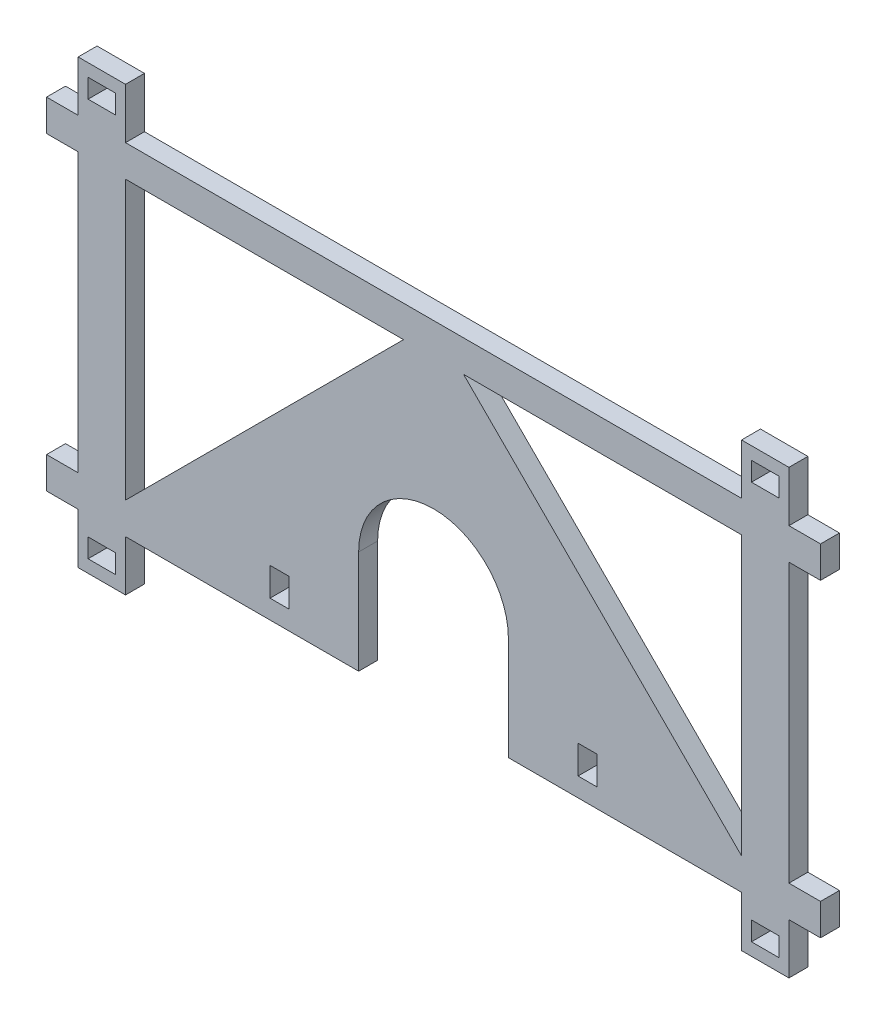
SolidWorks part; units mm, degrees
ref_plane "Front Plane" through (0, 0, 0) normal (0, 0, 1) x (1, 0, 0)
ref_plane "Top Plane" through (0, 0, 0) normal (0, 1, 0) x (1, 0, 0)
ref_plane "Right Plane" through (0, 0, 0) normal (1, 0, 0) x (0, 0, -1)
sketch "Sketch1" plane through (0, 0, 0) normal (0, 0, 1) x (1, 0, 0)
  line L0 (198.9667, 91.44) -> (198.9667, 82.9733)
  line L5 (198.9667, 82.9733) -> (190.5, 82.9733)
  line L6 (190.5, 0) -> (198.9667, 0)
  line L7 (198.9667, 0) -> (198.9667, 8.4667)
  line L8 (198.9667, 8.4667) -> (190.5, 8.4667)
  line L9 (-8.4667, 91.44) -> (-8.4667, 82.9733)
  line L10 (-8.4667, 82.9733) -> (0, 82.9733)
  line L11 (-8.4667, 91.44) -> (0, 91.44)
  line L12 (0, 0) -> (-8.4667, 0)
  line L13 (-8.4667, 0) -> (-8.4667, 8.4667)
  line L14 (-8.4667, 8.4667) -> (0, 8.4667)
  line L15 (0, 91.44) -> (0, 82.9733) construction
  line L16 (190.5, 91.44) -> (190.5, 82.9733) construction
  line L17 (190.5, 8.4667) -> (190.5, 0) construction
  line L18 (0, 8.4667) -> (0, 0) construction
  line L19 (198.9667, 91.44) -> (190.5, 91.44)
  line L20 (0, 82.9733) -> (0, 8.4667)
  line L21 (190.5, 82.9733) -> (190.5, 8.4667)
  line L22 (0, 0) -> (0, -13.5467)
  line L23 (0, -13.5467) -> (12.7, -13.5467)
  line L24 (12.7, -13.5467) -> (12.7, 0)
  line L25 (190.5, 0) -> (190.5, -13.5467)
  line L26 (190.5, -13.5467) -> (177.8, -13.5467)
  line L27 (177.8, -13.5467) -> (177.8, 0)
  line L28 (190.5, 91.44) -> (190.5, 104.9867)
  line L29 (190.5, 104.9867) -> (177.8, 104.9867)
  line L30 (177.8, 104.9867) -> (177.8, 91.44)
  line L31 (0, 91.44) -> (0, 104.9867)
  line L32 (0, 104.9867) -> (12.7, 104.9867)
  line L33 (12.7, 104.9867) -> (12.7, 91.44)
  line L34 (0, 91.44) -> (12.7, 91.44) construction
  line L35 (177.8, 91.44) -> (190.5, 91.44) construction
  line L36 (177.8, 0) -> (190.5, 0) construction
  line L37 (0, 0) -> (12.7, 0) construction
  line L38 (12.7, 91.44) -> (177.8, 91.44)
  line L39 (12.7, 0) -> (177.8, 0)
  dimension "D1" = 190.5
  dimension "D2" = 91.44
  dimension "D3" = 8.4667
  dimension "D4" = 8.4667
  dimension "D5" = 13.5467
  dimension "D6" = 12.7
extrude "Boss-Extrude1" add sketch "Sketch1" along normal blind 5.08
sketch "Sketch2" plane through (0, 0, 5.08) normal (0, 0, 1) x (1, 0, 0)
  line L0 (95.25, 0) -> (95.25, 47.752) construction
  line L1 (12.7, 0) -> (177.8, 0) construction
  line L2 (95.25, 0) -> (115.316, 0)
  line L3 (115.316, 0) -> (115.316, 27.686)
  line L5 (75.184, 27.686) -> (75.184, 0)
  line L6 (95.25, 0) -> (75.184, 0)
  line L7 (75.184, 0) -> (115.316, 0) construction
  arc A0 (115.316, 27.686) -> (75.184, 27.686) centre (95.25, 27.686) ccw
  dimension "D1" = 47.752
  dimension "D2" = 20.066
extrude "Cut-Extrude2" cut sketch "Sketch2" against normal through all
sketch "Sketch3" plane through (0, 0, 5.08) normal (0, 0, 1) x (1, 0, 0)
  line L0 (177.8, 91.44) -> (190.5, 91.44) construction
  line L1 (177.8, 0) -> (190.5, 0) construction
  line L2 (0, 0) -> (12.7, 0) construction
  line L3 (0, 91.44) -> (12.7, 91.44) construction
  line L4 (6.35, 91.44) -> (6.35, 96.52) construction
  line L5 (184.15, 91.44) -> (184.15, 96.52) construction
  line L6 (184.15, 0) -> (184.15, -5.08) construction
  line L7 (6.35, 0) -> (6.35, -5.08) construction
  line L8 (6.35, 96.52) -> (10.033, 96.52)
  line L9 (10.033, 96.52) -> (10.033, 101.6)
  line L10 (10.033, 101.6) -> (2.667, 101.6)
  line L11 (2.667, 101.6) -> (2.667, 96.52)
  line L12 (2.667, 96.52) -> (6.35, 96.52)
  line L13 (184.15, 96.52) -> (187.833, 96.52)
  line L14 (187.833, 96.52) -> (187.833, 101.6)
  line L15 (187.833, 101.6) -> (180.467, 101.6)
  line L16 (180.467, 101.6) -> (180.467, 96.52)
  line L17 (180.467, 96.52) -> (184.15, 96.52)
  line L18 (184.15, -5.08) -> (187.833, -5.08)
  line L19 (187.833, -5.08) -> (187.833, -10.16)
  line L20 (187.833, -10.16) -> (180.467, -10.16)
  line L21 (180.467, -10.16) -> (180.467, -5.08)
  line L22 (180.467, -5.08) -> (184.15, -5.08)
  line L23 (6.35, -5.08) -> (10.033, -5.08)
  line L24 (10.033, -5.08) -> (10.033, -10.16)
  line L25 (10.033, -10.16) -> (2.667, -10.16)
  line L26 (2.667, -10.16) -> (2.667, -5.08)
  line L27 (2.667, -5.08) -> (6.35, -5.08)
  dimension "D1" = 5.08
  dimension "D2" = 5.08
  dimension "D3" = 3.683
extrude "Cut-Extrude4" cut sketch "Sketch3" against normal through all
sketch "Sketch4" plane through (0, 0, 5.08) normal (0, 0, 1) x (1, 0, 0)
  line L0 (12.7, 0) -> (53.975, 0) construction
  line L1 (12.7, 0) -> (75.184, 0) construction
  line L2 (53.975, 0) -> (95.25, 0) construction
  line L3 (95.25, 0) -> (136.525, 0) construction
  line L4 (115.316, 0) -> (177.8, 0) construction
  line L5 (136.525, 0) -> (177.8, 0) construction
  line L6 (53.975, 0) -> (53.975, 5.08) construction
  line L7 (136.525, 0) -> (136.525, 5.08) construction
  line L8 (136.525, 5.08) -> (139.065, 5.08)
  line L9 (139.065, 5.08) -> (139.065, 12.7)
  line L10 (139.065, 12.7) -> (133.985, 12.7)
  line L11 (133.985, 12.7) -> (133.985, 5.08)
  line L12 (133.985, 5.08) -> (136.525, 5.08)
  line L13 (53.975, 5.08) -> (56.515, 5.08)
  line L14 (56.515, 5.08) -> (56.515, 12.7)
  line L15 (56.515, 12.7) -> (51.435, 12.7)
  line L16 (51.435, 12.7) -> (51.435, 5.08)
  line L17 (51.435, 5.08) -> (53.975, 5.08)
  dimension "D1" = 5.08
  dimension "D2" = 2.54
  dimension "D3" = 7.62
extrude "Cut-Extrude5" cut sketch "Sketch4" against normal through all
sketch "Sketch5" plane through (0, 0, 5.08) normal (0, 0, 1) x (1, 0, 0)
  line L0 (0, 82.9733) -> (12.7, 82.9733) construction
  line L1 (12.7, 82.9733) -> (12.7, 91.44) construction
  line L2 (0, 8.4667) -> (12.7, 8.4667) construction
  line L3 (12.7, 8.4667) -> (12.7, 0) construction
  line L4 (12.7, 82.9733) -> (12.7, 8.4667)
  line L5 (12.7, 8.4667) -> (87.2067, 82.9733)
  line L6 (87.2067, 82.9733) -> (12.7, 82.9733)
extrude "Cut-Extrude6" cut sketch "Sketch5" against normal through all contours L6 L4 L5
ref_plane "Plane1" through (95.25, 0, 0) normal (1, 0, 0) x (0, 0, -1)
mirror "Mirror1" about plane through (95.25, 0, 0) normal (1, 0, 0) of "Cut-Extrude6"
equation "\"FoamCore\" = \".2\""
equation "\"MDF\" = \".2\""
equation "\"GMaterial\"= \".2\""
equation "\"PVCMountDiameter\" = \"0.5in\""
equation "\"PVCMountDistanceToEdge\" = \"0.5\""
equation "\"PVCThickness\" = \"0.13in\""
equation "\"PVCDiameter\" = 1.5in"
equation "\"BaseWidth\" = \"8in\""
equation "\"BaseLength\" = \"10in\""
equation "\"BallDiameter\" = \"38mm\""
equation "\"BaseGap\" = \"4in\""
equation "\"FunnelTopDiameter\" = \"8in\""
equation "\"FunnelTopDepth\" = \"0.5in\""
equation "\"BallGap\" = \"0.1in\""
equation "\"FunnelLength\" = 3in"
equation "\"FunnelMaterial\" = 0.1in"
equation "\"FunnelLowerDiameter\" = 1.9in"
equation "\"FunnelDepth\" = 1.5in"
equation "\"FunnelBendLength\" = 2*pi*\"FunnelLowerDiameter\"/2*135"
equation "\"AmmoFeederLength\" = 1.5in + 76mm"
equation "\"WheelThickness\" = 0.5in"
equation "\"LauncherWheelDiameter\" = 76mm"
equation "\"MotorFrontLength\" = 0.95in"
equation "\"MotorBodyTotalLength\" = 2.03in"
equation "\"MotorFrontDiameter\" = 1.5in"
equation "\"MotorLowerDriveshaftDiameter\" = 0.46in"
equation "\"MotorLowerDriveshaftThickness\" = 0.25in"
equation "\"MotorFullDriveshaftLength\" = 0.78in"
equation "\"MotorDriveshaftDiameter\" = 0.23in"
equation "\"MotorDriveshaftFlatThickness\" = 0.2in"
equation "\"MotorRearDiameter\" = 31.9mm"
equation "\"MotorDriveshaftBottomToTop\" = 31.1mm"
equation "\"MotorFlatDriveshaftLength\" = 11.7mm"
equation "\"MotorDistanceBetweenLowerandTopHoles\" = 0.5in"
equation "\"MotorMountsDistanceFromEdge\" = 0.06in"
equation "\"MotorScrewMountDiameter\" = 0.1in"
equation "\"MotorScrewMountDepth\" = 0.13in"
equation "\"HBRidgeScrewHoleDeep\" = 0.18in"
equation "\"MotorMountWidth\" = \"1.61in\""
equation "\"MotorMountLength\" = \"1.58in\""
equation "\"MotorMountToEdgeGap\" = \"3.3mm\""
equation "\"MotorMountToInsideEdgeGap\" = \"6.5mm\""
equation "\"MotorMountToMountWidthGap\" = \"25.8mm\""
equation "\"MotorMountToMountLengthGap\" = \"20.5mm\""
equation "\"MotorMountMaterialThickness\" = 1.6mm"
equation "\"MotorMountBaseScrewholeDiameter\" = 3.8mm"
equation "\"MotorMountBaseDistancebetweenHoles\" = 0.8in"
equation "\"MotorMountHeight\" = 1.85in"
equation "\"HBridgeWidth\" = 2.25in"
equation "\"HBridgeLength\" = 1.40in"
equation "\"UnoWidth\" = 3.13in"
equation "\"UnoLength\" = 3.06in"
equation "\"BatteryWidth\" = 1.15in"
equation "\"BatteryLength\" = 3.86in"
equation "\"ScrewDiameter\" = 2.7mm"
equation "\"MotorMountFaceScrewtoBase\" = 0.46in"
equation "\"MotorMountFaceDistanceBetweenScrews\" = 0.95in"
equation "\"MotorMountFaceMiddletoEdge\" = 0.16in"
equation "\"MotorMountFaceBottomtoEdge\" = 0.42in"
equation "\"MotorMountCenterholeHeight\" = 1.04in"
equation "\"MotorMountCenterholetoEdge\" = 0.25in"
equation "\"MovingWheelDiameter\" = 76mm"
equation "\"MovingWheelThickness\" = 0.5in"
equation "\"BraceLength\" = 1in"
equation "\"BraceVerticalOffset\" = 3.5in"
equation "\"BraceHorizontalOffset\" = 2.5in"
equation "\"BaseToBaseDistance\" = 3.6in"
equation "\"PVCOutsideDiameter\" = \"PVCDiameter\" + 2*\"PVCThickness\""
equation "\"D1@Sketch1\"=\"BraceVerticalOffset\"*2+\"BraceLength\"/2"
equation "\"D2@Sketch1\"=\"BaseToBaseDistance\""
equation "\"D3@Sketch1\"=\"BraceLength\"/3"
equation "\"D4@Sketch1\"=\"BraceLength\"/3"
equation "\"D5@Sketch1\"=\"MDF\"+\"BraceLength\"/3"
equation "\"D6@Sketch1\"=\"BraceLength\"/2"
equation "\"D1@Boss-Extrude1\"=\"MDF\""
equation "\"D1@Sketch2\"=\"MotorMountHeight\"+0.03"
equation "\"D2@Sketch2\"=\"MotorMountLength\"/2"
equation "\"D1@Sketch3\"=\"MDF\""
equation "\"D2@Sketch3\"=\"MDF\""
equation "\"AmmoFeederCutoffLength\"= \"MovingWheelDiameter\""
equation "\"Distancebetweenwalls\" = 6in"
equation "\"Slidewidth\" = 0.3in"
equation "\"Slidelength\" = 0.8in"
equation "\"D3@Sketch3\"=\"Slidewidth\"/2-0.005"
equation "\"Bottomtofloor\" = 0.53in"
equation "\"tabdistance\" = 0.2in"
equation "\"tabwidth\" = 0.3in"
equation "\"D1@Sketch4\"=\"tabdistance\""
equation "\"D2@Sketch4\"=\"MDF\"/2"
equation "\"D3@Sketch4\"=\"tabwidth\""
